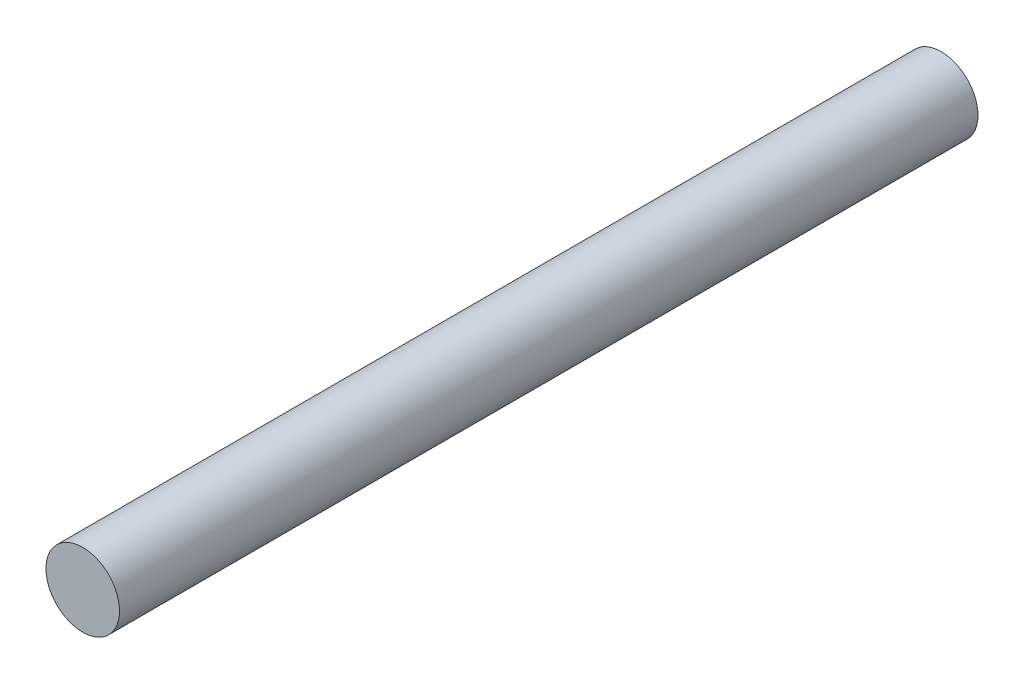
SolidWorks part; units mm, degrees
ref_plane "Front Plane" through (0, 0, 0) normal (0, 0, 1) x (1, 0, 0)
ref_plane "Top Plane" through (0, 0, 0) normal (0, 1, 0) x (1, 0, 0)
ref_plane "Right Plane" through (0, 0, 0) normal (1, 0, 0) x (0, 0, -1)
sketch "Sketch1" plane through (0, 0, 0) normal (0, 0, 1) x (1, 0, 0)
  circle A0 centre (0, 0) radius 3
extrude "Boss-Extrude1" add sketch "Sketch1" along normal blind 70
